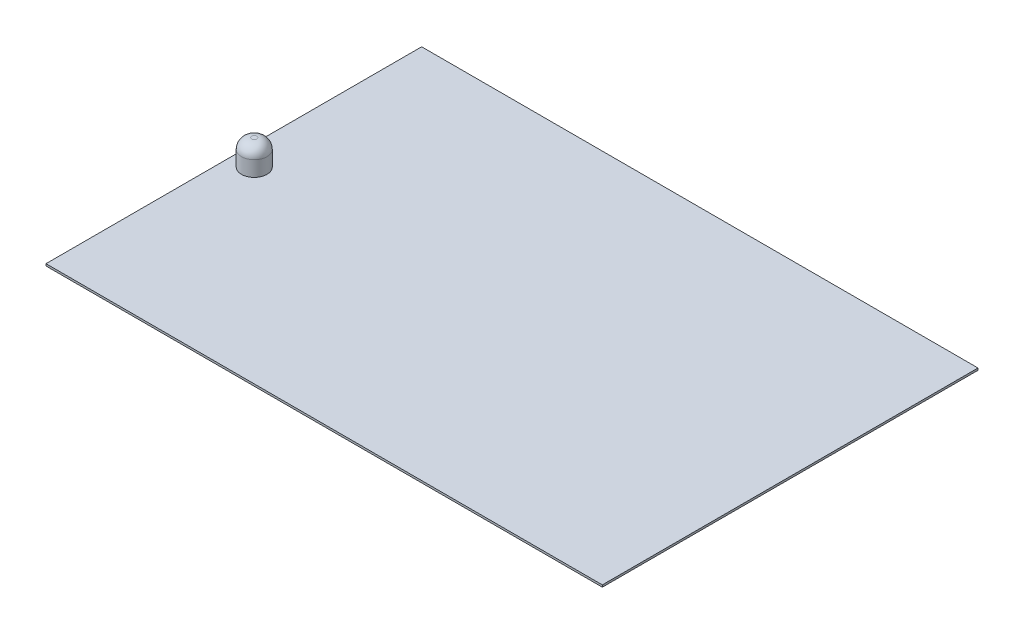
SolidWorks part; units mm, degrees
ref_plane "Alzado" through (0, 0, 0) normal (0, 0, 1) x (1, 0, 0)
ref_plane "Planta" through (0, 0, 0) normal (0, 1, 0) x (1, 0, 0)
ref_plane "Vista lateral" through (0, 0, 0) normal (1, 0, 0) x (0, 0, -1)
sketch "Croquis1" plane through (0, 0, 0) normal (0, 1, 0) x (1, 0, 0)
  line L1 (272.5, -184) -> (-272.5, -184)
  line L2 (272.5, -184) -> (272.5, 184)
  line L3 (272.5, 184) -> (-272.5, 184)
  line L4 (-272.5, -184) -> (-272.5, 184)
  line L5 (272.5, -184) -> (-272.5, 184) construction
  line L6 (272.5, 184) -> (-272.5, -184) construction
  point P0 (0, 0)
  dimension "D1" = 545
  dimension "D2" = 368
extrude "Extruir1" add sketch "Croquis1" along normal blind 2
sketch "Croquis2" plane through (0, 2, 0) normal (0, 1, 0) x (1, 0, 0)
  line L0 (-252.5, 184) -> (-252.5, -184) construction
  line L1 (272.5, 184) -> (-272.5, 184) construction
  line L2 (-272.5, -184) -> (272.5, -184) construction
  line L3 (-272.5, 184) -> (-272.5, -184) construction
  line L4 (-252.5, 0) -> (-272.5, 0) construction
  circle A0 centre (-252.5, 0) radius 12.5
  dimension "D2" = 25
  dimension "D1" = 20
extrude "Extruir2" add sketch "Croquis2" along normal blind 25 separate body
fillet "Redondeo1" radius 10 1 edges at (-252.5, 27, 12.5)
